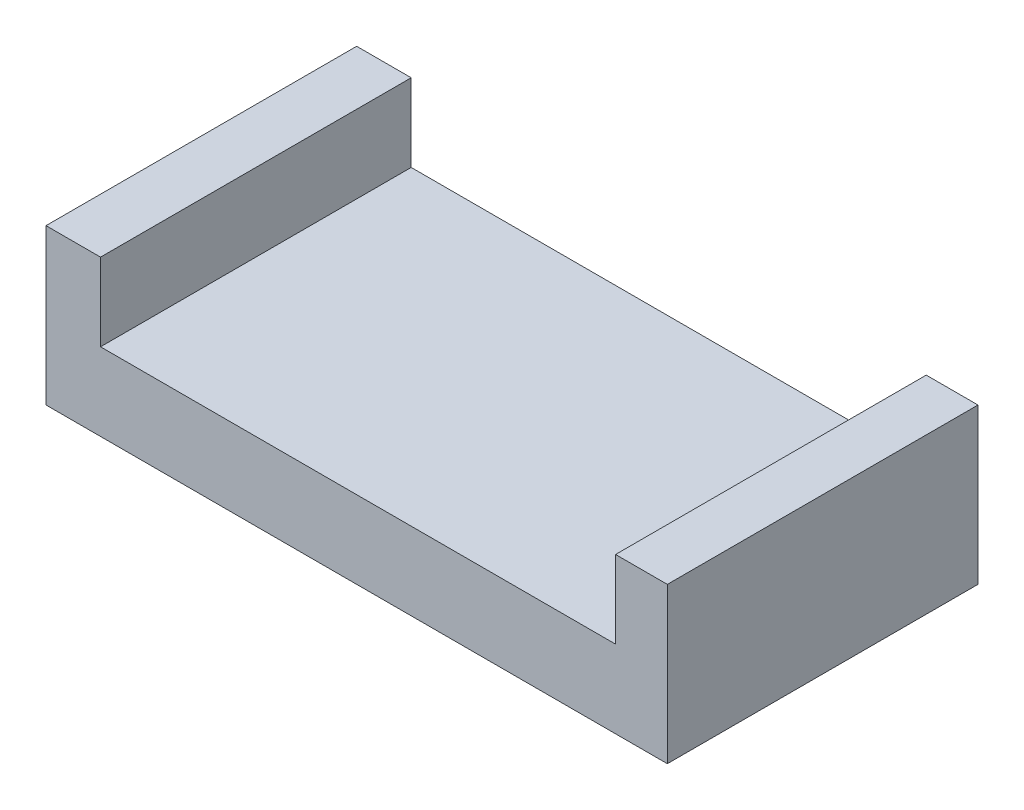
SolidWorks part; units mm, degrees
ref_plane "Front Plane" through (0, 0, 0) normal (0, 0, 1) x (1, 0, 0)
ref_plane "Top Plane" through (0, 0, 0) normal (0, 1, 0) x (1, 0, 0)
ref_plane "Right Plane" through (0, 0, 0) normal (1, 0, 0) x (0, 0, -1)
sketch "Sketch1" plane through (0, 0, 0) normal (0, 1, 0) x (1, 0, 0)
  line L1 (7.62, -3.81) -> (-7.62, -3.81)
  line L2 (7.62, -3.81) -> (7.62, 3.81)
  line L3 (7.62, 3.81) -> (-7.62, 3.81)
  line L4 (-7.62, -3.81) -> (-7.62, 3.81)
  line L5 (7.62, -3.81) -> (-7.62, 3.81) construction
  line L6 (7.62, 3.81) -> (-7.62, -3.81) construction
  point P0 (0, 0)
  dimension "D1" = 15.24
  dimension "D2" = 7.62
extrude "Boss-Extrude1" add sketch "Sketch1" along normal blind 1.905
sketch "Sketch2" plane through (0, 1.905, 0) normal (0, 1, 0) x (1, 0, 0)
  line L5 (7.62, 3.81) -> (-7.62, 3.81) construction
  line L6 (-7.62, -3.81) -> (-6.2824, -3.81)
  line L7 (-7.62, -3.81) -> (-7.62, 3.81)
  line L8 (-7.62, 3.81) -> (-6.2824, 3.81)
  line L9 (-6.2824, -3.81) -> (-6.2824, 3.81)
extrude "Boss-Extrude2" add sketch "Sketch2" along normal blind 1.905
sketch "Sketch3" plane through (0, 1.905, 0) normal (0, 1, 0) x (1, 0, 0)
  line L0 (-6.2824, -3.81) -> (7.62, -3.81) construction
  line L1 (7.62, 3.81) -> (6.35, 3.81)
  line L2 (7.62, 3.81) -> (7.62, -3.81)
  line L3 (7.62, -3.81) -> (6.35, -3.81)
  line L4 (6.35, 3.81) -> (6.35, -3.81)
  dimension "D1" = 1.27
extrude "Boss-Extrude3" add sketch "Sketch3" along normal blind 1.905
